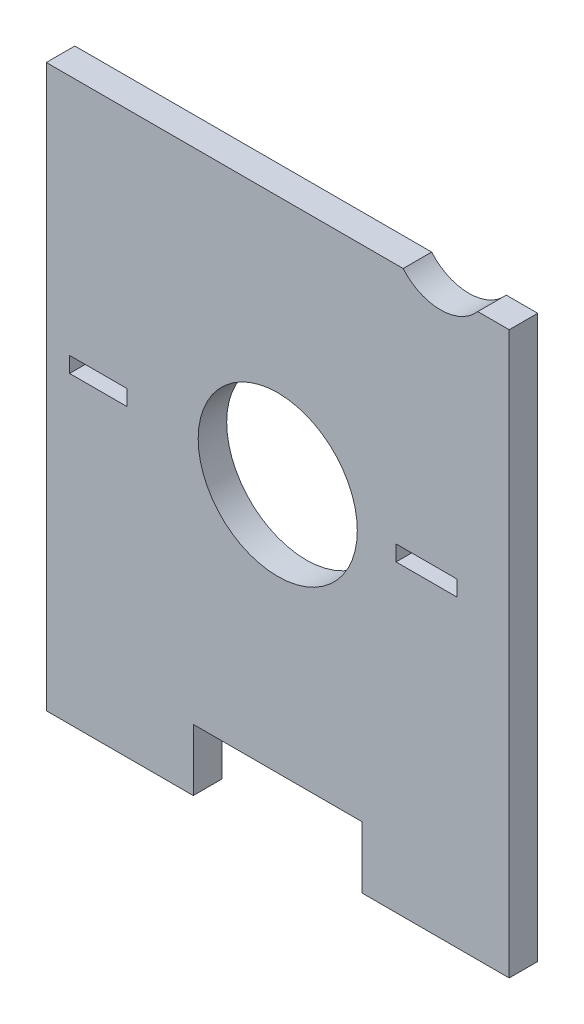
SolidWorks part; units mm, degrees
ref_plane "Front Plane" through (0, 0, 0) normal (0, 0, 1) x (1, 0, 0)
ref_plane "Top Plane" through (0, 0, 0) normal (0, 1, 0) x (1, 0, 0)
ref_plane "Right Plane" through (0, 0, 0) normal (1, 0, 0) x (0, 0, -1)
sketch "Sketch1" plane through (0, 0, 0) normal (0, 0, 1) x (1, 0, 0)
  line L1 (0, 0) -> (40, 0)
  line L2 (0, 0) -> (0, 43.18)
  line L3 (0, 43.18) -> (40, 43.18)
  line L4 (40, 0) -> (40, 43.18)
  dimension "D1" = 40
  dimension "D2" = 43.18
extrude "Base" add sketch "Sketch1" along normal blind 2.4638
sketch "Sketch2" plane through (0, 0, 0) normal (0, -1, 0) x (1, 0, 0)
  line L0 (0, 2.4638) -> (40, 2.4638) construction
  line L1 (0, 0) -> (12.7, 0)
  line L2 (0, 0) -> (0, 2.4638)
  line L3 (0, 2.4638) -> (12.7, 2.4638)
  line L4 (12.7, 0) -> (12.7, 2.4638)
  line L5 (27.3, 1.2319) -> (12.7, 1.2319) construction
  line L6 (40, 0) -> (27.3, 0)
  line L7 (40, 0) -> (40, 2.4638)
  line L8 (40, 2.4638) -> (27.3, 2.4638)
  line L9 (27.3, 0) -> (27.3, 2.4638)
  dimension "D1" = 12.7
extrude "Bottom Tabs" add sketch "Sketch2" along normal blind 5.334
sketch "Sketch3" plane through (0, 0, 2.4638) normal (0, 0, 1) x (1, 0, 0)
  line L0 (35.4853, 20.9142) -> (35.4853, 22.2658) construction
  line L1 (35.4853, 22.2658) -> (30.2236, 22.2658) construction
  line L2 (30.2236, 22.2658) -> (30.2236, 20.9142) construction
  line L3 (30.2236, 20.9142) -> (35.4853, 20.9142) construction
  line L4 (2.0127, 22.2658) -> (2.0127, 20.9142) construction
  line L5 (2.0127, 20.9142) -> (6.9873, 20.9142) construction
  line L6 (6.9873, 20.9142) -> (6.9873, 22.2658) construction
  line L7 (6.9873, 22.2658) -> (2.0127, 22.2658) construction
  line L8 (35.4853, 20.9142) -> (35.4853, 22.2658)
  line L9 (35.4853, 22.2658) -> (30.2236, 22.2658)
  line L10 (30.2236, 22.2658) -> (30.2236, 20.9142)
  line L11 (30.2236, 20.9142) -> (35.4853, 20.9142)
  line L12 (2.0127, 22.2658) -> (2.0127, 20.9142)
  line L13 (2.0127, 20.9142) -> (6.9873, 20.9142)
  line L14 (6.9873, 20.9142) -> (6.9873, 22.2658)
  line L15 (6.9873, 22.2658) -> (2.0127, 22.2658)
  circle A0 centre (20, 21.59) radius 6.875 construction
  circle A1 centre (20, 21.59) radius 6.875
extrude "Mount Points" cut sketch "Sketch3" against normal through all
extrude "Cut-Extrude2" cut sketch "Sketch4" against normal through all
sketch "Sketch4" plane through (18.2464, 22.2936, 2.4638) normal (0, 0, 1) x (1, 0, 0)
  circle A2 centre (15.8136, 23.6491) radius 2.975 construction
  circle A3 centre (15.8136, 23.6491) radius 4.245
equation "\"material\"= \"acrylic_sm@base.assembly\""
equation "\"D1@Base\"=\"material\""
equation "\"D1@Bottom Tabs\"=\"mdf@base.assembly\""
